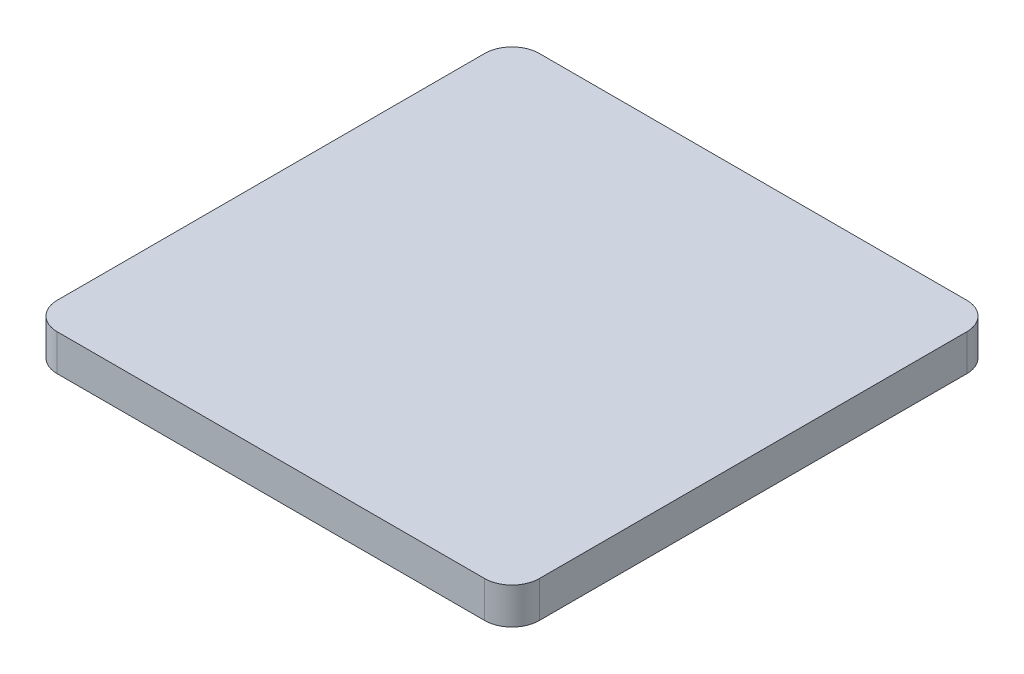
SolidWorks part; units mm, degrees
ref_plane "Front Plane" through (0, 0, 0) normal (0, 0, 1) x (1, 0, 0)
ref_plane "Top Plane" through (0, 0, 0) normal (0, 1, 0) x (1, 0, 0)
ref_plane "Right Plane" through (0, 0, 0) normal (1, 0, 0) x (0, 0, -1)
sketch "Sketch1" plane through (0, 0, 0) normal (0, 1, 0) x (1, 0, 0)
  line L1 (0, 0) -> (53, 0)
  line L2 (0, 0) -> (0, 53)
  line L3 (0, 53) -> (53, 53)
  line L4 (53, 0) -> (53, 53)
  dimension "D1" = 53
  dimension "D2" = 53
extrude "Boss-Extrude1" add sketch "Sketch1" along normal blind 4
fillet "Fillet2" radius 3 4 edges at (0, 2, -53) (0, 2, 0) (53, 2, -53) (53, 2, 0)
